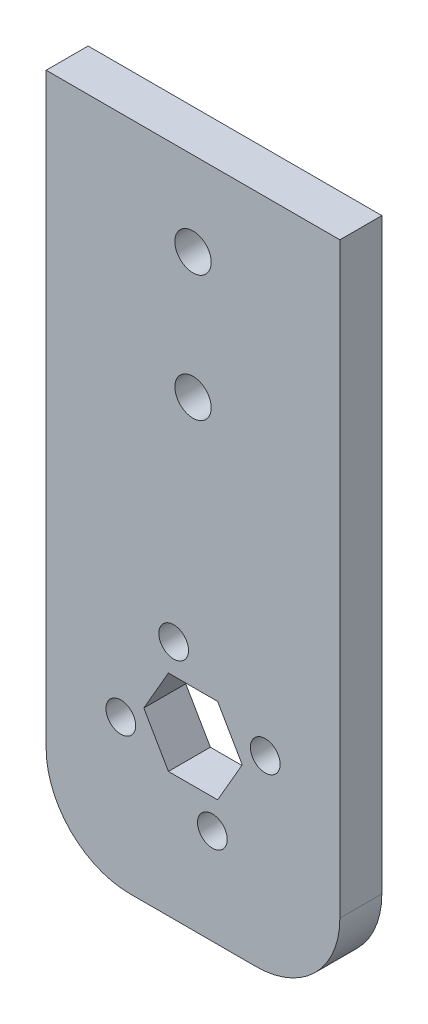
SolidWorks part; units mm, degrees
material "6061 Alloy"
ref_plane "Front Plane" through (0, 0, 0) normal (0, 0, 1) x (1, 0, 0)
ref_plane "Top Plane" through (0, 0, 0) normal (0, 1, 0) x (1, 0, 0)
ref_plane "Right Plane" through (0, 0, 0) normal (1, 0, 0) x (0, 0, -1)
sketch "Sketch1" plane through (0, 0, 0) normal (0, 0, 1) x (1, 0, 0)
  line L1 (0, 0) -> (-44.45, 0)
  line L2 (0, 0) -> (0, 101.6)
  line L3 (0, 101.6) -> (-44.45, 101.6)
  line L4 (-44.45, 0) -> (-44.45, 101.6)
  dimension "D1" = 101.6
  dimension "D2" = 44.45
extrude "Boss-Extrude2" add sketch "Sketch1" along normal blind 6.35
sketch "Sketch3" plane through (0, 0, 0) normal (0, 0, -1) x (-1, 0, 0)
  line L0 (22.225, 101.6) -> (22.225, 0) construction
  line L1 (0, 101.6) -> (44.45, 101.6) construction
  line L2 (44.45, 0) -> (0, 0) construction
  point P3 (22.225, 50.8)
fillet "Fillet1" radius 12.7 2 edges at (-44.45, 0, 3.175) (0, 0, 3.175)
hole_wizard "M5 Clearance Hole1" positions "Sketch11" profile "Sketch12" hole size "M5" standard "ANSI Metric" end condition through all
sketch "Sketch11" plane through (0, 0, 0) normal (0, 0, -1) x (-1, 0, 0)
  line L0 (22.225, 101.6) -> (22.225, 0) construction
  line L1 (0, 101.6) -> (44.45, 101.6) construction
  point P0 (22.225, 88.9)
  point P4 (22.225, 69.85)
  dimension "D1" = 19.05
  dimension "D2" = 12.7
sketch "Sketch12" plane through (-22.225, 88.9, 0) normal (1, 0, 0) x (0, 1, 0)
  line L0 (0, 0) -> (0, 6.35)
  line L1 (0, 6.35) -> (2.75, 6.35)
  line L2 (2.75, 6.35) -> (2.75, 0)
  line L5 (2.75, 0) -> (0, 0)
  line L11 (0, -6.35) -> (0, 107.95) construction
  dimension "Thru Hole Dia." = 5.5
  dimension "Thru Hole Depth" = 6.35
sketch "Sketch14" plane through (0, 0, 6.35) normal (0, 0, 1) x (1, 0, 0)
  line L0 (-22.225, 101.6) -> (-22.225, 0) construction
  line L1 (-14.7772, 25.4) -> (-18.5011, 31.85)
  line L2 (-18.5011, 31.85) -> (-25.9489, 31.85)
  line L3 (-25.9489, 31.85) -> (-29.6728, 25.4)
  line L4 (-29.6728, 25.4) -> (-25.9489, 18.95)
  line L5 (-25.9489, 18.95) -> (-18.5011, 18.95)
  line L6 (-18.5011, 18.95) -> (-14.7772, 25.4)
  line L7 (-31.75, 0) -> (-12.7, 0) construction
  circle A0 centre (-22.225, 25.4) radius 6.45 construction
  point P12 (-22.225, 31.85)
  dimension "D1" = 12.9
  dimension "D2" = 25.4
extrude "Cut-Extrude1" cut sketch "Sketch14" against normal through all
sketch "Sketch22" plane through (0, 0, 6.35) normal (0, 0, 1) x (1, 0, 0)
  circle A0 centre (-25.1532, 36.3282) radius 2.05
  circle A1 centre (-11.2968, 28.3282) radius 2.05
  circle A2 centre (-19.2968, 14.4718) radius 2.05
  circle A3 centre (-33.1532, 22.4718) radius 2.05
hole_wizard "M4 Clearance Hole1" positions "Sketch25" profile "Sketch24" hole size "M4" standard "ANSI Metric" end condition through all
sketch "Sketch25" plane through (0, 0, 0) normal (0, 0, -1) x (-1, 0, 0)
  point P0 (11.2968, 28.3282)
  point P3 (25.1532, 36.3282)
  point P6 (33.1532, 22.4718)
  point P9 (19.2968, 14.4718)
sketch "Sketch24" plane through (-11.2968, 28.3282, 0) normal (1, 0, 0) x (0, 1, 0)
  line L0 (0, 0) -> (0, 6.35)
  line L1 (0, 6.35) -> (2.25, 6.35)
  line L2 (2.25, 6.35) -> (2.25, 0)
  line L5 (2.25, 0) -> (0, 0)
  line L11 (0, -6.35) -> (0, 107.95) construction
  dimension "Thru Hole Dia." = 4.5
  dimension "Thru Hole Depth" = 6.35
